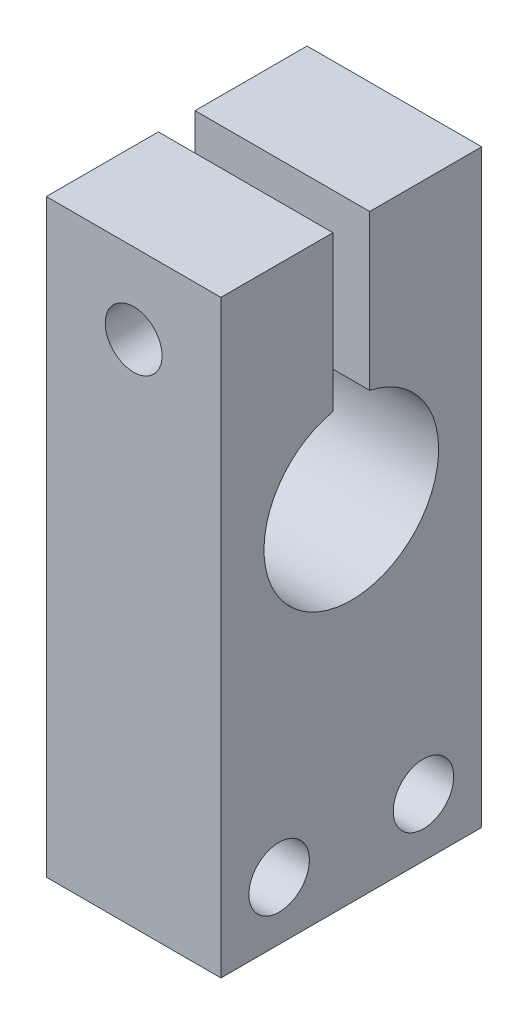
SolidWorks part; units mm, degrees
material "6061 Alloy"
ref_plane "Front Plane" through (0, 0, 0) normal (0, 0, 1) x (1, 0, 0)
ref_plane "Top Plane" through (0, 0, 0) normal (0, 1, 0) x (1, 0, 0)
ref_plane "Right Plane" through (0, 0, 0) normal (1, 0, 0) x (0, 0, -1)
ref_plane "Plane1" through (4.7625, 0, 0) normal (1, 0, 0) x (0, 0, -1)
sketch "Sketch1" plane through (4.7625, 0, 0) normal (1, 0, 0) x (0, 0, -1)
  line L0 (15.875, -19.05) -> (15.875, 13.1064)
  line L1 (15.875, 13.1064) -> (-15.875, 13.1064)
  line L2 (-15.875, 13.1064) -> (-15.875, -19.05)
  line L3 (-15.875, -19.05) -> (15.875, -19.05)
  dimension "D1" = 31.75
  dimension "D2" = 32.1564
  dimension "D3" = 13.1064
  dimension "D4" = 15.875
extrude "Boss-Extrude1" add sketch "Sketch1" against normal blind 9.525
sketch "Sketch2" plane through (-4.7625, 0, 0) normal (-1, 0, 0) x (0, 0, 1)
  line L0 (-7.112, -19.05) -> (-7.112, 13.1064)
  line L1 (-7.112, 13.1064) -> (-15.875, 13.1064)
  line L2 (-15.875, 13.1064) -> (-15.875, -19.05)
  line L3 (-15.875, -19.05) -> (-7.112, -19.05)
  line L4 (15.875, -19.05) -> (-15.875, -19.05) construction
  line L5 (-15.875, 13.1064) -> (15.875, 13.1064) construction
  line L6 (-15.875, -19.05) -> (-15.875, 13.1064) construction
  dimension "D1" = 8.763
extrude "Cut-Extrude1" cut sketch "Sketch2" against normal through all
sketch "Sketch3" plane through (-4.7625, 0, 0) normal (-1, 0, 0) x (0, 0, 1)
  line L0 (1.0033, 13.1064) -> (-1.0033, 13.1064)
  line L1 (-1.0033, 13.1064) -> (-1.0033, 4.6556)
  line L2 (1.0033, 4.6556) -> (1.0033, 13.1064)
  line L3 (-7.112, -19.05) -> (-7.112, 13.1064) construction
  line L4 (-7.112, 13.1064) -> (15.875, 13.1064) construction
  arc A0 (-1.0033, 4.6556) -> (1.0033, 4.6556) centre (0, 0) cw
  dimension "D1" = 4.7625
  dimension "D2" = 6.1087
  dimension "D3" = 7.112
  dimension "D4" = 8.4508
extrude "Cut-Extrude2" cut sketch "Sketch3" against normal through all
sketch "Sketch4" plane through (-4.7625, 0, 0) normal (-1, 0, 0) x (0, 0, 1)
  line L0 (7.112, -19.0536) -> (15.875, -19.0536)
  line L1 (15.875, -19.0536) -> (15.875, 13.1064)
  line L2 (15.875, 13.1064) -> (7.112, 13.1064)
  line L3 (7.112, 13.1064) -> (7.112, -19.0536)
  line L4 (1.0033, 4.6556) -> (1.0033, 13.1064) construction
  line L5 (1.0033, 13.1064) -> (15.875, 13.1064) construction
  dimension "D1" = 6.1087
  dimension "D2" = 14.8717
  dimension "D3" = 32.16
extrude "Cut-Extrude3" cut sketch "Sketch4" against normal through all
sketch "Sketch5" plane through (0, 0, 0) normal (0, 0, 1) x (1, 0, 0)
  line L0 (-4.7625, 4.7625) -> (-4.7625, 0)
  line L1 (-4.7625, 0) -> (4.7625, 0)
  line L2 (4.7625, 0) -> (4.7625, 4.7625)
  line L3 (4.7625, 4.7625) -> (-4.7625, 4.7625)
  line L4 (-4.7625, 0) -> (4.7625, 0) construction
  dimension "D1" = 4.7625
  dimension "D2" = 4.7625
  dimension "D3" = 4.7625
revolve "Cut-Revolve1" cut sketch "Sketch5" angle 360 about L4
hole_wizard "Hole1" positions "Sketch7" profile "Sketch6" legacy
sketch "Sketch7" plane through (0, 0, 1.0033) normal (0, 0, -1) x (-1, 0, 0)
  point P0 (0, 8.7376)
sketch "Sketch6" plane through (0, 8.7376, 1.0033) normal (1, 0, 0) x (0, 1, 0)
  line L0 (0, 0) -> (0, 6.1087)
  line L1 (0, 6.1087) -> (1.3208, 6.1087)
  line L2 (1.3208, 6.1087) -> (1.3208, 0)
  line L3 (1.3208, 0) -> (0, 0)
  line L4 (0, 110) -> (0, -10) construction
  dimension "Diameter" = 2.6416
  dimension "Depth" = 6.1087
hole_wizard "CBORE for M2.5 Hex Head Machine Screw1" positions "Sketch9" profile "Sketch8" counterbore size "M2.5" standard "ANSI Metric" end condition through all
sketch "Sketch9" plane through (0, 0, -7.112) normal (0, 0, -1) x (-1, 0, 0)
  point P0 (0, 8.7376)
sketch "Sketch8" plane through (0, 8.7376, -7.112) normal (1, 0, 0) x (0, 1, 0)
  line L0 (0, 0) -> (0, 14.224)
  line L1 (0, 14.224) -> (1.55, 14.224)
  line L3 (1.55, 14.224) -> (1.55, 2.1)
  line L4 (1.55, 2.1) -> (3.64, 2.1)
  line L5 (3.64, 2.1) -> (3.64, 0)
  line L7 (3.64, 0) -> (0, 0)
  line L11 (0, -6.35) -> (0, 107.95) construction
  dimension "Thru Hole Dia." = 3.1
  dimension "Thru Hole Depth" = 14.224
  dimension "C'Bore Dia." = 7.28
  dimension "C'Bore Depth" = 2.1
hole_wizard "M4x0.7 Tapped Hole1" positions "Sketch11" profile "Sketch10" tap size "M4x0.7" standard "ANSI Metric" end condition through all
sketch "Sketch11" plane through (4.7625, -17.4625, 0) normal (-1, 0, 0) x (0, 1, 0)
  line L3 (-1.5875, -7.112) -> (-1.5875, 7.112) construction
  line L4 (-1.5875, 7.112) -> (30.5689, 7.112) construction
  line L5 (30.5689, -7.112) -> (-1.5875, -7.112) construction
  point P2 (1.5875, 3.937)
  point P4 (1.5875, -3.937)
  dimension "D1" = 3.175
  dimension "D2" = 3.175
  dimension "D3" = 3.175
sketch "Sketch10" plane through (4.7625, -15.875, -3.937) normal (0, 1, 0) x (0, 0, -1)
  line L0 (0, 0) -> (0, 9.525)
  line L1 (0, 9.525) -> (1.65, 9.525)
  line L2 (1.65, 9.525) -> (1.65, 0)
  line L5 (1.65, 0) -> (0, 0)
  line L11 (0, -6.35) -> (0, 107.95) construction
  dimension "Thru Tap Drill Dia." = 3.3
  dimension "Thru Tap Drill Depth" = 9.525
